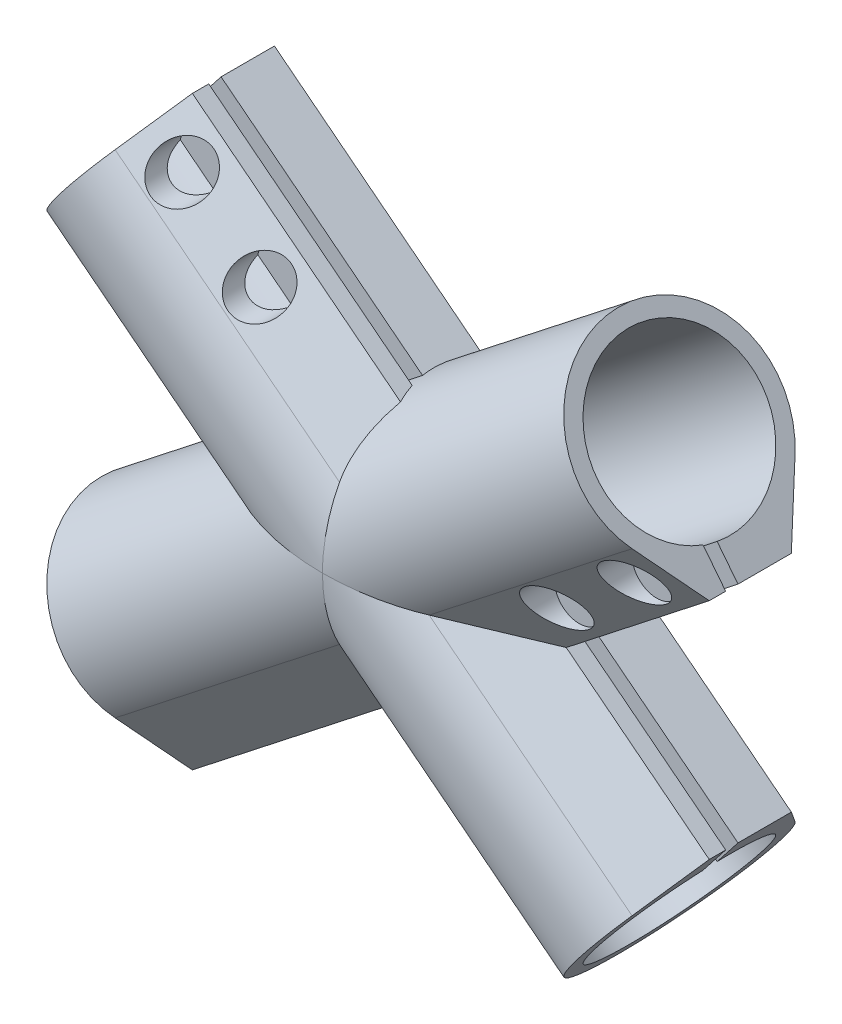
SolidWorks part; units mm, degrees
ref_plane "Plan de face" through (0, 0, 0) normal (0, 0, 1) x (1, 0, 0)
ref_plane "Plan de dessus" through (0, 0, 0) normal (0, 1, 0) x (1, 0, 0)
ref_plane "Plan de droite" through (0, 0, 0) normal (1, 0, 0) x (0, 0, -1)
sketch "Esquisse2" plane through (0, 0, 0) normal (0, 0, 1) x (1, 0, 0)
  line L0 (0, 0) -> (46.001, 0) construction
  line L1 (46.001, 0) -> (46.001, 36.041) construction
  line L2 (46.001, 36.041) -> (0, 0) construction
  line L3 (0, 0) -> (46.001, -36.041) construction
  line L4 (31.4868, 24.6694) -> (36.9365, 17.7137) construction
  line L5 (31.4868, -24.6694) -> (36.9365, -17.7137) construction
  point P5 (46.001, -36.041)
  dimension "D1" = 36.041
  dimension "D2" = 46.001
  dimension "D3" = 40
ref_plane "Plan2" through (31.4868, 24.6694, 0) normal (-0.7872, -0.6167, 0) x (0, 0, 1)
sketch "Esquisse4" plane through (31.4868, 24.6694, 0) normal (-0.7872, -0.6167, 0) x (0, 0, 1)
  line L0 (0, -28.3704) -> (0, 0) construction
  line B0 (-9.9285, -6.7398) -> (-5, -14)
  line B1 (-5, -14) -> (1.5, -14)
  line B2 (1.5, -14) -> (1.5, -9.8869)
  line B3 (3, -9.5394) -> (3, -14)
  line B4 (3, -14) -> (5, -14)
  line B5 (5, -14) -> (9.9285, -6.7398)
  arc B6 (9.9285, -6.7398) -> (-9.9285, -6.7398) centre (0, 0) ccw
  arc B7 (3, -9.5394) -> (1.5, -9.8869) centre (0, 0) ccw
sketch_block_instance "Bloc1-1"
sketch_block "Bloc1"
extrude "Boss.-Extru.1" add sketch "Esquisse4" along normal blind 80
ref_plane "Plan3" through (31.4868, -24.6694, 0) normal (0.7872, -0.6167, 0) x (0, 0, -1)
sketch "Esquisse5" plane through (31.4868, -24.6694, 0) normal (0.7872, -0.6167, 0) x (0, 0, -1)
  point P0 (-1.5, 14)
  line B0 (9.9285, 6.7398) -> (5, 14)
  line B1 (5, 14) -> (-1.5, 14)
  line B2 (-1.5, 14) -> (-1.5, 9.8869)
  line B3 (-3, 9.5394) -> (-3, 14)
  line B4 (-3, 14) -> (-5, 14)
  line B5 (-5, 14) -> (-9.9285, 6.7398)
  arc B6 (-9.9285, 6.7398) -> (9.9285, 6.7398) centre (0, 0) ccw
  arc B7 (-3, 9.5394) -> (-1.5, 9.8869) centre (0, 0) ccw
sketch_block_instance "Bloc1-2"
extrude "Boss.-Extru.2" add sketch "Esquisse5" against normal blind 80
sketch "Esquisse6" plane through (31.4868, 24.6694, 0) normal (0.7872, 0.6167, 0) x (0, 0, -1)
  circle A0 centre (0, 0) radius 10
  arc A1 (-1.5, -9.8869) -> (-3, -9.5394) centre (0, 0) ccw construction
extrude "Enlèv. mat.-Extru.1" cut sketch "Esquisse6" against normal through all
sketch "Esquisse7" plane through (31.4868, -24.6694, 0) normal (0.7872, -0.6167, 0) x (0, 0, -1)
  circle A0 centre (0, 0) radius 10
  arc A1 (-3, 9.5394) -> (-1.5, 9.8869) centre (0, 0) ccw construction
extrude "Enlèv. mat.-Extru.2" cut sketch "Esquisse7" against normal through all
ref_plane "Plan4" through (0, 0, 3) normal (0, 0, -1) x (-1, 0, 0)
sketch "Esquisse8" plane through (0, 0, 3) normal (0, 0, -1) x (-1, 0, 0)
  line L0 (21.3836, 29.4574) -> (11.9376, 22.0566) construction
  line L1 (-33.7183, 13.714) -> (-24.2723, 6.3132) construction
  line L2 (-22.7002, 0) -> (-40.1211, 13.649) construction
  line L3 (22.8525, 35.6898) -> (-2.5062, 15.8217) construction
  line L4 (-35.6435, 19.364) -> (-40.1211, 13.649) construction
  line L5 (27.3301, 29.9748) -> (22.8525, 35.6898) construction
  circle A0 centre (21.3836, 29.4574) radius 3
  circle A1 centre (11.9376, 22.0566) radius 3
  circle A2 centre (-24.2723, 6.3132) radius 3
  circle A3 centre (-33.7183, 13.714) radius 3
  dimension "D7" = 6
  dimension "D1" = 12
  dimension "D2" = 12
  dimension "D3" = 5
  dimension "D4" = 5
  dimension "D5" = 4
  dimension "D6" = 4
extrude "Enlèv. mat.-Extru.3" cut sketch "Esquisse8" against normal blind 10 from offset 2 offset against normal yes
